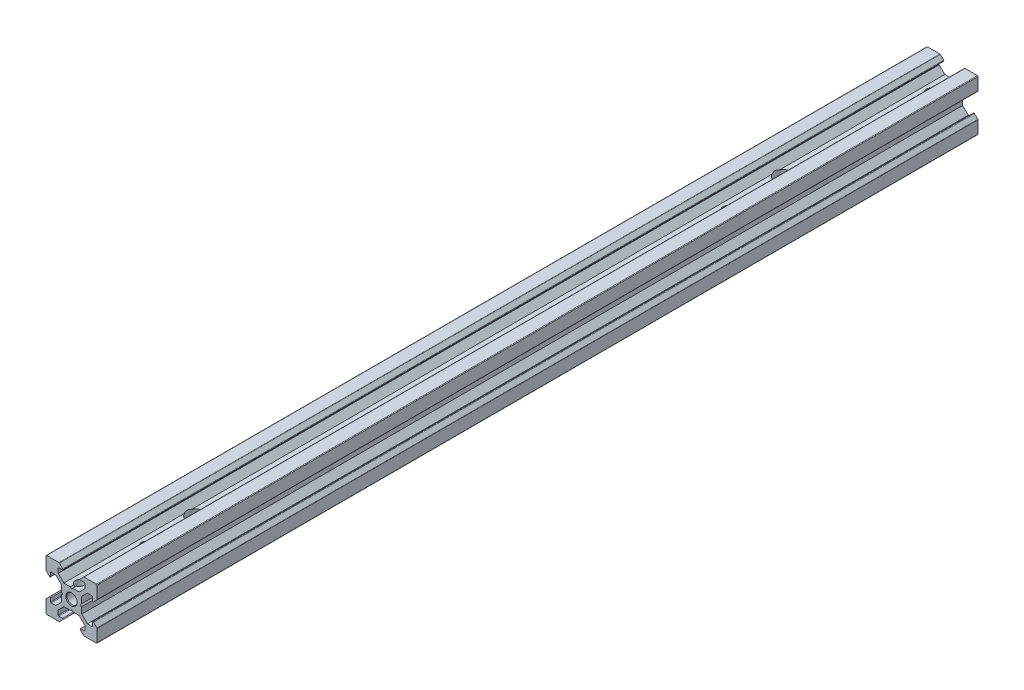
SolidWorks part; units mm, degrees
material "3.0205 (EN-AW 1200)"
ref_plane "Alzado" through (0, 0, 0) normal (0, 0, 1) x (1, 0, 0)
ref_plane "Planta" through (0, 0, 0) normal (0, 1, 0) x (1, 0, 0)
ref_plane "Vista lateral" through (0, 0, 0) normal (1, 0, 0) x (0, 0, -1)
sketch "Croquis1" plane through (0, 0, 0) normal (0, 0, 1) x (1, 0, 0)
  line L0 (-3.9878, 0.4994) -> (-3.4878, -0.0006)
  line L43 (0.0115, 3.5003) -> (-0.4882, 4)
  line L44 (-0.4882, 4) -> (-2.9967, 4)
  line L45 (-2.9967, 4) -> (-5.1969, 6.2003)
  line L46 (-5.1969, 6.2003) -> (-5.1969, 7.9432)
  line L47 (-4.9469, 8.1932) -> (-3.6023, 8.1932)
  line L53 (-7.9369, 5.2103) -> (-6.1869, 5.2103)
  line L54 (-6.1869, 5.2103) -> (-3.9878, 3.0113)
  line L55 (-3.9878, 3.0113) -> (-3.9878, 0.4994)
  line L58 (-8.1869, 4.9603) -> (-8.1869, 3.602)
  line L60 (-9.9869, 9.7494) -> (-9.9869, 4.902)
  line L61 (-9.7369, 9.9994) -> (-4.9084, 9.9994)
  line L62 (-8.6137, 3.4252) -> (-9.9137, 4.7252)
  line L64 (6.2124, 5.2094) -> (7.9554, 5.2094)
  line L65 (-3.4255, 8.62) -> (-4.7316, 9.9261)
  line L66 (4.0122, 3.0091) -> (6.2124, 5.2094)
  line L67 (4.0122, 0.5007) -> (4.0122, 3.0091)
  line L68 (3.5124, 0.001) -> (4.0122, 0.5007)
  line L71 (0.5115, 4.0003) -> (0.0115, 3.5003)
  line L72 (3.0234, 4.0003) -> (0.5115, 4.0003)
  line L73 (5.2225, 6.1994) -> (3.0234, 4.0003)
  line L74 (5.2225, 7.9494) -> (5.2225, 6.1994)
  line L75 (4.9725, 8.1994) -> (3.6141, 8.1994)
  line L76 (3.4374, 8.6261) -> (4.7374, 9.9261)
  line L77 (9.7615, 9.9994) -> (4.9141, 9.9994)
  line L78 (10.0115, 9.7494) -> (10.0115, 4.9208)
  line L79 (8.6322, 3.4379) -> (9.9383, 4.744)
  line L80 (8.2054, 4.9594) -> (8.2054, 3.6147)
  line L81 (5.2216, -6.2) -> (5.2216, -7.9429)
  line L82 (3.0213, -3.9997) -> (5.2216, -6.2)
  line L83 (0.5128, -3.9997) -> (3.0213, -3.9997)
  line L84 (0.0131, -3.5) -> (0.5128, -3.9997)
  line L87 (4.0124, -0.499) -> (3.5124, 0.001)
  line L88 (4.0124, -3.011) -> (4.0124, -0.499)
  line L89 (6.2115, -5.21) -> (4.0124, -3.011)
  line L90 (7.9615, -5.21) -> (6.2115, -5.21)
  line L91 (8.2115, -4.96) -> (8.2115, -3.6017)
  line L92 (8.6383, -3.4249) -> (9.9383, -4.7249)
  line L93 (10.0115, -9.749) -> (10.0115, -4.9017)
  line L94 (9.7615, -9.999) -> (4.933, -9.999)
  line L95 (3.4501, -8.6197) -> (4.7562, -9.9258)
  line L96 (4.9716, -8.1929) -> (3.6269, -8.1929)
  line L97 (-6.1878, -5.2091) -> (-7.9308, -5.2091)
  line L98 (-3.9876, -3.0088) -> (-6.1878, -5.2091)
  line L99 (-3.9876, -0.5004) -> (-3.9876, -3.0088)
  line L100 (-3.4878, -0.0006) -> (-3.9876, -0.5004)
  line L103 (-0.4869, -4) -> (0.0131, -3.5)
  line L104 (-2.9988, -4) -> (-0.4869, -4)
  line L105 (-5.1247, -6.1258) -> (-2.9988, -4)
  line L106 (-5.1979, -7.949) -> (-5.1979, -6.3026)
  line L107 (-4.9479, -8.199) -> (-3.5895, -8.199)
  line L108 (-3.4127, -8.6258) -> (-4.7127, -9.9258)
  line L109 (-9.7369, -9.999) -> (-4.8895, -9.999)
  line L110 (-9.9869, -9.749) -> (-9.9869, -4.9205)
  line L111 (-8.6076, -3.4376) -> (-9.9137, -4.7437)
  line L112 (-8.1808, -4.9591) -> (-8.1808, -3.6144)
  arc A0 (10.0115, -9.749) -> (9.7615, -9.999) centre (9.7615, -9.749) cw
  arc A1 (-9.7369, -9.999) -> (-9.9869, -9.749) centre (-9.7369, -9.749) cw
  arc A2 (10.0115, 9.7494) -> (9.7615, 9.9994) centre (9.7615, 9.7494) ccw
  arc A3 (-9.7369, 9.9994) -> (-9.9869, 9.7494) centre (-9.7369, 9.7494) ccw
  arc A4 (8.2115, -3.6017) -> (8.6383, -3.4249) centre (8.4615, -3.6017) cw
  arc A5 (7.9615, -5.21) -> (8.2115, -4.96) centre (7.9615, -4.96) ccw
  arc A6 (5.2216, -7.9429) -> (4.9716, -8.1929) centre (4.9716, -7.9429) cw
  arc A7 (3.4501, -8.6197) -> (3.6269, -8.1929) centre (3.6269, -8.4429) cw
  arc A8 (-3.5895, -8.199) -> (-3.4127, -8.6258) centre (-3.5895, -8.449) cw
  arc A9 (-5.1979, -7.949) -> (-4.9479, -8.199) centre (-4.9479, -7.949) ccw
  arc A10 (-5.1247, -6.1258) -> (-5.1979, -6.3026) centre (-4.9479, -6.3026) ccw
  arc A11 (-7.9308, -5.2091) -> (-8.1808, -4.9591) centre (-7.9308, -4.9591) cw
  arc A12 (-8.6076, -3.4376) -> (-8.1808, -3.6144) centre (-8.4308, -3.6144) cw
  arc A13 (8.6322, 3.4379) -> (8.2054, 3.6147) centre (8.4554, 3.6147) cw
  arc A14 (7.9554, 5.2094) -> (8.2054, 4.9594) centre (7.9554, 4.9594) cw
  arc A15 (5.2225, 7.9494) -> (4.9725, 8.1994) centre (4.9725, 7.9494) ccw
  arc A16 (3.6141, 8.1994) -> (3.4374, 8.6261) centre (3.6141, 8.4494) cw
  arc A17 (-3.6023, 8.1932) -> (-3.4255, 8.62) centre (-3.6023, 8.4432) ccw
  arc A18 (-8.6137, 3.4252) -> (-8.1869, 3.602) centre (-8.4369, 3.602) ccw
  arc A19 (-5.1969, 7.9432) -> (-4.9469, 8.1932) centre (-4.9469, 7.9432) cw
  arc A20 (-8.1869, 4.9603) -> (-7.9369, 5.2103) centre (-7.9369, 4.9603) cw
  arc A21 (9.9383, -4.7249) -> (10.0115, -4.9017) centre (9.7615, -4.9017) cw
  arc A22 (4.933, -9.999) -> (4.7562, -9.9258) centre (4.933, -9.749) cw
  arc A23 (10.0115, 4.9208) -> (9.9383, 4.744) centre (9.7615, 4.9208) cw
  arc A24 (4.7374, 9.9261) -> (4.9141, 9.9994) centre (4.9141, 9.7494) cw
  arc A25 (-4.7316, 9.9261) -> (-4.9084, 9.9994) centre (-4.9084, 9.7494) ccw
  arc A26 (-9.9137, 4.7252) -> (-9.9869, 4.902) centre (-9.7369, 4.902) cw
  arc A27 (-9.9869, -4.9205) -> (-9.9137, -4.7437) centre (-9.7369, -4.9205) cw
  arc A28 (-4.7127, -9.9258) -> (-4.8895, -9.999) centre (-4.8895, -9.749) cw
  dimension "D2" = 0.25
  dimension "D3" = 0.25
  dimension "D4" = 0.25
  dimension "D1" = 4
extrude "Saliente-Extruir1" add sketch "Croquis1" along normal blind 172.5 and the other way blind 172.5
sketch "Croquis7" plane through (0, 0, 172.5) normal (0, 0, 1) x (1, 0, 0)
  circle A0 centre (0, 0) radius 2
  dimension "D1" = 4
extrude "Cortar-Extruir1" cut sketch "Croquis7" against normal through all
chamfer "Chaflán1" distance 0.25 angle 45 2 edges at (2, 0, -172.5) (2, 0, 172.5)
ref_plane "Plano2" through (0, 9.9994, 0) normal (0, 1, 0) x (1, 0, 0)
ref_plane "Plano3" through (0, -9.999, 0) normal (0, -1, 0) x (-1, 0, 0)
sketch "Croquis11" plane through (0, 9.9994, 0) normal (0, 1, 0) x (1, 0, 0)
  line L0 (-15.4971, -172.5) -> (15.8808, -172.5) construction
  line L1 (0.0115, -177.8961) -> (0.0115, 177.9047) construction
  line L2 (-14.9235, 172.5) -> (13.9023, 172.5) construction
sketch "Croquis12" plane through (0, -9.999, 0) normal (0, -1, 0) x (-1, 0, 0)
  line L0 (-15.8808, -172.5) -> (15.4971, -172.5) construction
  line L1 (-0.0115, -177.8961) -> (-0.0115, 177.9047) construction
  line L2 (-13.9023, 172.5) -> (14.9235, 172.5) construction
sketch "Croquis13" plane through (0, 9.9994, 0) normal (0, 1, 0) x (1, 0, 0)
  line L0 (0.0115, -177.8961) -> (0.0115, 177.9047) construction
  line L1 (-15.4971, -172.5) -> (15.8808, -172.5) construction
  point P0 (0.0115, -169.5)
  point P1 (0.0115, -143.5)
  point P4 (0.0115, 84.2)
  point P5 (0.0115, 163.9)
  dimension "D1" = 3
  dimension "D2" = 79.7
  dimension "D3" = 227.7
  dimension "D4" = 26
hole_wizard "Diámetro de taladro Ø3.3 (3.3)1" positions "Croquis14" profile "Croquis15" hole size "Ø3.3" standard "Ansi Metric"
sketch "Croquis14" plane through (0, 9.9994, 0) normal (0, 1, 0) x (1, 0, 0)
  point P0 (0.0115, -143.5)
  point P3 (0.0115, -169.5)
  point P6 (0.0115, 84.2)
  point P9 (0.0115, 163.9)
sketch "Croquis15" plane through (0.0115, 9.9994, 143.5) normal (1, 0, 0) x (0, 0, 1)
  line L0 (0, 0) -> (0, 7.9994)
  line L1 (0, 7.9994) -> (1.65, 7.9994)
  line L2 (1.65, 7.9994) -> (1.65, 0)
  line L5 (1.65, 0) -> (0, 0)
  line L11 (0, -6.35) -> (0, 107.95) construction
  dimension "Diámetro de taladro hasta el siguiente" = 3.3
  dimension "Profundidad de taladro hasta el siguiente" = 7.9994
sketch "Croquis16" plane through (0, -9.999, 0) normal (0, -1, 0) x (-1, 0, 0)
  line L0 (-15.8808, -172.5) -> (15.4971, -172.5) construction
  point P0 (0, -123.9)
  point P1 (0, 106.3)
  dimension "D1" = 48.6
  dimension "D2" = 230.2
hole_wizard "Refrentado para tornillo con cabeza plana de M61" positions "Croquis17" profile "Croquis19" counterbore size "M6" standard "ISO" end condition through all
sketch "Croquis17" plane through (0, -9.999, 0) normal (0, -1, 0) x (-1, 0, 0)
  point P0 (0, -123.9)
  point P3 (0, 106.3)
sketch "Croquis19" plane through (0, -9.999, 123.9) normal (1, 0, 0) x (0, 0, -1)
  line L0 (0, 0) -> (0, 19.9984)
  line L1 (0, 19.9984) -> (3.3, 19.9984)
  line L3 (3.3, 19.9984) -> (3.3, 3.9)
  line L4 (3.3, 3.9) -> (5.5, 3.9)
  line L5 (5.5, 3.9) -> (5.5, 0)
  line L7 (5.5, 0) -> (0, 0)
  line L11 (0, -6.35) -> (0, 107.95) construction
  dimension "Diámetro de taladro hasta el siguiente" = 6.6
  dimension "Profundidad de taladro hasta el siguiente" = 19.9984
  dimension "Diámetro de refrentado" = 11
  dimension "Profundidad de refrentado" = 3.9
